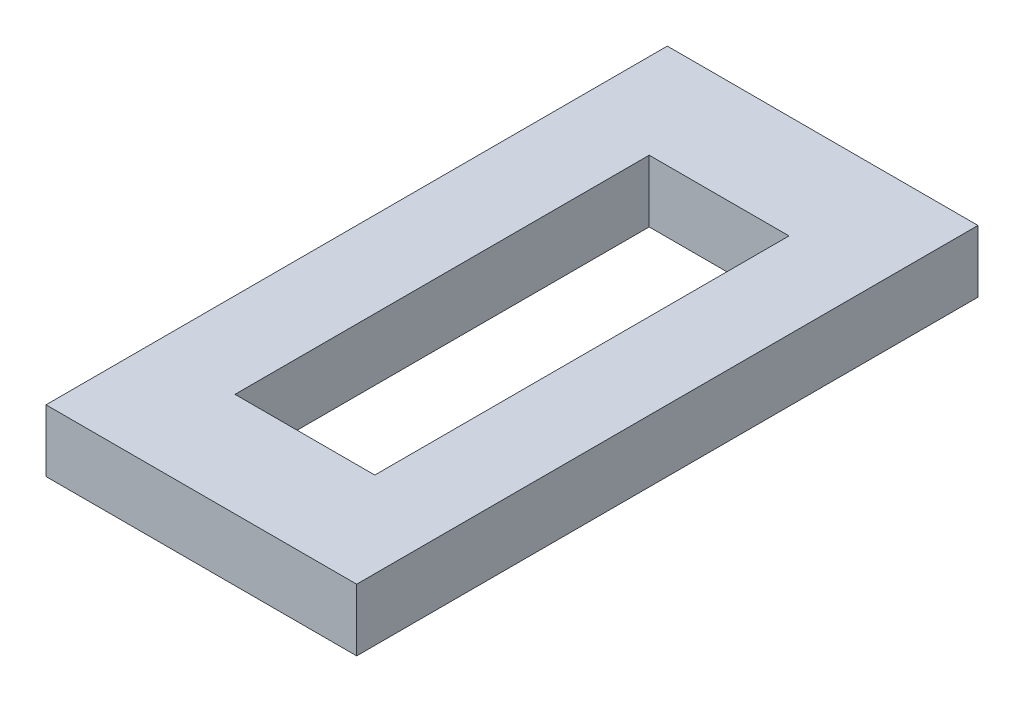
SolidWorks part; units mm, degrees
ref_plane "Front Plane" through (0, 0, 0) normal (0, 0, 1) x (1, 0, 0)
ref_plane "Top Plane" through (0, 0, 0) normal (0, 1, 0) x (1, 0, 0)
ref_plane "Right Plane" through (0, 0, 0) normal (1, 0, 0) x (0, 0, -1)
sketch "Sketch1" plane through (0, 0, 0) normal (0, 1, 0) x (1, 0, 0)
  line L1 (-15, 30) -> (15, 30)
  line L2 (-15, 30) -> (-15, -30)
  line L3 (-15, -30) -> (15, -30)
  line L4 (15, 30) -> (15, -30)
  line L5 (-15, 30) -> (15, -30) construction
  line L6 (-15, -30) -> (15, 30) construction
  line L7 (-6.75, 20) -> (6.75, 20)
  line L8 (-6.75, 20) -> (-6.75, -20)
  line L9 (-6.75, -20) -> (6.75, -20)
  line L10 (6.75, 20) -> (6.75, -20)
  line L11 (-6.75, 20) -> (6.75, -20) construction
  line L12 (-6.75, -20) -> (6.75, 20) construction
  point P0 (0, 0)
  point P6 (0, 0)
  dimension "D1" = 60
  dimension "D2" = 30
  dimension "D3" = 13.5
  dimension "D4" = 40
extrude "Boss-Extrude1" add sketch "Sketch1" along normal blind 6
